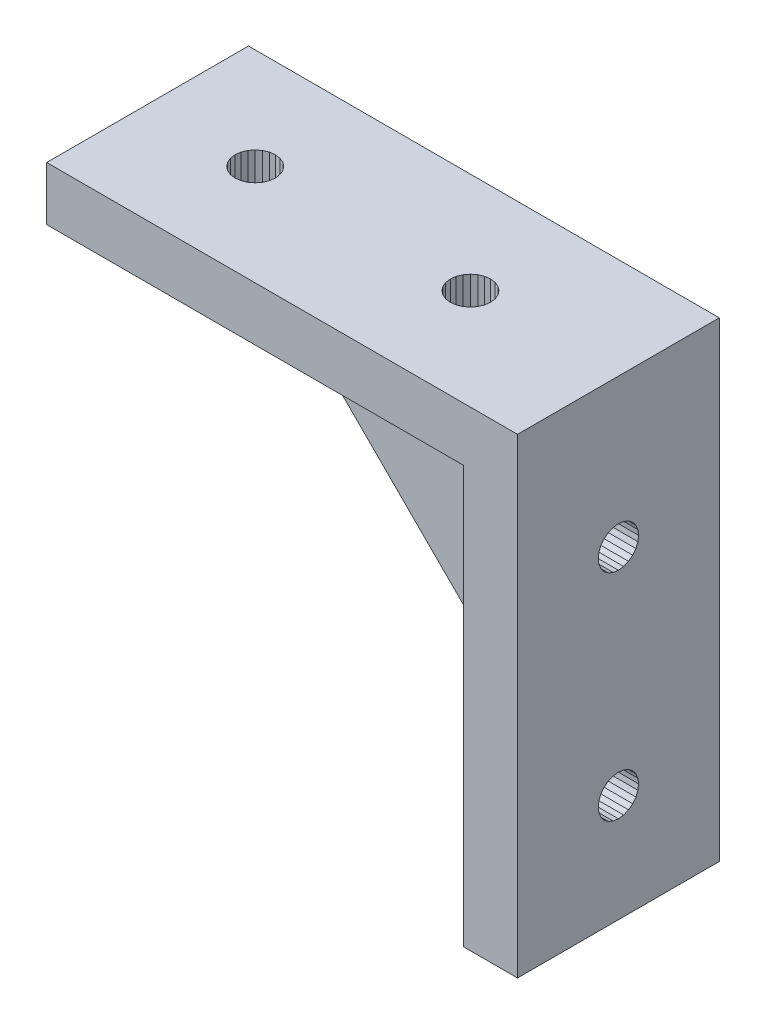
SolidWorks part; units mm, degrees
ref_plane "Front Plane" through (0, 0, 0) normal (0, 0, 1) x (1, 0, 0)
ref_plane "Top Plane" through (0, 0, 0) normal (0, 1, 0) x (1, 0, 0)
ref_plane "Right Plane" through (0, 0, 0) normal (1, 0, 0) x (0, 0, -1)
ref_plane "Plane4" through (0, 0, 10) normal (0, 0, -1) x (-1, 0, 0)
sketch "Sketch1" plane through (0, 0, 10) normal (0, 0, -1) x (-1, 0, 0)
  line L0 (-25, -35) -> (10, -35)
  line L1 (10, -35) -> (10, -4)
  line L2 (10, -4) -> (-25, -4)
  line L3 (-25, -4) -> (-25, -35)
  dimension "D1" = 35
  dimension "D2" = 31
extrude "Boss-Extrude1" add sketch "Sketch1" against normal blind 15
sketch "Sketch2" plane through (0, 0, 10) normal (0, 0, -1) x (-1, 0, 0)
  line L0 (10, -4) -> (-21, -35)
  line L1 (-21, -35) -> (10, -35)
  line L2 (10, -35) -> (10, -4)
  line L3 (-25, -4) -> (-25, -35) construction
  line L4 (-25, -35) -> (10, -35) construction
  dimension "D1" = 4
  dimension "D2" = 35
  dimension "D3" = 31
extrude "Cut-Extrude1" cut sketch "Sketch2" against normal blind 4
sketch "Sketch3" plane through (0, -4, 0) normal (0, 1, 0) x (-1, 0, 0)
  line L0 (10, 10) -> (-25, 10)
  line L1 (-25, 10) -> (-25, 25)
  line L2 (-25, 25) -> (10, 25)
  line L3 (10, 25) -> (10, 10)
  line L4 (10, 25) -> (10, 14) construction
  line L5 (10, 10) -> (-25, 10) construction
  dimension "D1" = 35
  dimension "D2" = 15
extrude "Boss-Extrude2" add sketch "Sketch3" along normal blind 4
sketch "Sketch4" plane through (-10, 0, 0) normal (-1, 0, 0) x (0, 0, 1)
  line L0 (25, -35) -> (25, -4)
  line L1 (25, -4) -> (14, -4)
  line L2 (14, -4) -> (14, -35)
  line L3 (14, -35) -> (25, -35)
  line L4 (25, -35) -> (25, 0) construction
  line L5 (25, -35) -> (14, -35) construction
  dimension "D1" = 11
  dimension "D2" = 31
extrude "Cut-Extrude2" cut sketch "Sketch4" against normal blind 31
sketch "Sketch5" plane through (0, -4, 0) normal (0, -1, 0) x (1, 0, 0)
  line L0 (-2.75, 16.201) -> (-2.3882, 16.0511)
  line L1 (-2.3882, 16.0511) -> (-2, 16)
  line L2 (-2, 16) -> (-1.6118, 16.0511)
  line L3 (-1.6118, 16.0511) -> (-1.25, 16.201)
  line L4 (-1.25, 16.201) -> (-0.9393, 16.4393)
  line L5 (-0.9393, 16.4393) -> (-0.701, 16.75)
  line L6 (-0.701, 16.75) -> (-0.5511, 17.1118)
  line L7 (-0.5511, 17.1118) -> (-0.5, 17.5)
  line L8 (-0.5, 17.5) -> (-0.5511, 17.8882)
  line L9 (-0.5511, 17.8882) -> (-0.701, 18.25)
  line L10 (-0.701, 18.25) -> (-0.9393, 18.5607)
  line L11 (-0.9393, 18.5607) -> (-1.25, 18.799)
  line L12 (-1.25, 18.799) -> (-1.6118, 18.9489)
  line L13 (-1.6118, 18.9489) -> (-2, 19)
  line L14 (-2, 19) -> (-2.3882, 18.9489)
  line L15 (-2.3882, 18.9489) -> (-2.75, 18.799)
  line L16 (-2.75, 18.799) -> (-3.0607, 18.5607)
  line L17 (-3.0607, 18.5607) -> (-3.299, 18.25)
  line L18 (-3.299, 18.25) -> (-3.4489, 17.8882)
  line L19 (-3.4489, 17.8882) -> (-3.5, 17.5)
  line L20 (-3.5, 17.5) -> (-3.4489, 17.1118)
  line L21 (-3.4489, 17.1118) -> (-3.299, 16.75)
  line L22 (-3.299, 16.75) -> (-3.0607, 16.4393)
  line L23 (-3.0607, 16.4393) -> (-2.75, 16.201)
  line L24 (-10, 25) -> (-10, 14) construction
  line L25 (21, 14) -> (-10, 14) construction
  dimension "D1" = 6.5
  dimension "D2" = 6.5511
  dimension "D3" = 6.701
  dimension "D4" = 6.9393
  dimension "D5" = 7.25
  dimension "D6" = 7.6118
  dimension "D7" = 8
  dimension "D8" = 8.3882
  dimension "D9" = 8.75
  dimension "D10" = 9.0607
  dimension "D11" = 9.299
  dimension "D12" = 9.4489
  dimension "D13" = 9.5
  dimension "D14" = 2
  dimension "D15" = 2.0511
  dimension "D16" = 2.201
  dimension "D17" = 2.4393
  dimension "D18" = 2.75
  dimension "D19" = 3.1118
  dimension "D20" = 3.5
  dimension "D21" = 3.8882
  dimension "D22" = 4.25
  dimension "D23" = 4.5607
  dimension "D24" = 4.799
  dimension "D25" = 4.9489
  dimension "D26" = 5
extrude "Cut-Extrude3" cut sketch "Sketch5" against normal through all
sketch "Sketch6" plane through (21, 0, 0) normal (-1, 0, 0) x (0, 0, 1)
  line L0 (17.1118, -28.4489) -> (17.5, -28.5)
  line L1 (17.5, -28.5) -> (17.8882, -28.4489)
  line L2 (17.8882, -28.4489) -> (18.25, -28.299)
  line L3 (18.25, -28.299) -> (18.5607, -28.0607)
  line L4 (18.5607, -28.0607) -> (18.799, -27.75)
  line L5 (18.799, -27.75) -> (18.9489, -27.3882)
  line L6 (18.9489, -27.3882) -> (19, -27)
  line L7 (19, -27) -> (18.9489, -26.6118)
  line L8 (18.9489, -26.6118) -> (18.799, -26.25)
  line L9 (18.799, -26.25) -> (18.5607, -25.9393)
  line L10 (18.5607, -25.9393) -> (18.25, -25.701)
  line L11 (18.25, -25.701) -> (17.8882, -25.5511)
  line L12 (17.8882, -25.5511) -> (17.5, -25.5)
  line L13 (17.5, -25.5) -> (17.1118, -25.5511)
  line L14 (17.1118, -25.5511) -> (16.75, -25.701)
  line L15 (16.75, -25.701) -> (16.4393, -25.9393)
  line L16 (16.4393, -25.9393) -> (16.201, -26.25)
  line L17 (16.201, -26.25) -> (16.0511, -26.6118)
  line L18 (16.0511, -26.6118) -> (16, -27)
  line L19 (16, -27) -> (16.0511, -27.3882)
  line L20 (16.0511, -27.3882) -> (16.201, -27.75)
  line L21 (16.201, -27.75) -> (16.4393, -28.0607)
  line L22 (16.4393, -28.0607) -> (16.75, -28.299)
  line L23 (16.75, -28.299) -> (17.1118, -28.4489)
  line L24 (14, -35) -> (25, -35) construction
  line L25 (25, -35) -> (25, -4) construction
  dimension "D1" = 6
  dimension "D2" = 6.0511
  dimension "D3" = 6.201
  dimension "D4" = 6.4393
  dimension "D5" = 6.75
  dimension "D6" = 7.1118
  dimension "D7" = 7.5
  dimension "D8" = 7.8882
  dimension "D9" = 8.25
  dimension "D10" = 8.5607
  dimension "D11" = 8.799
  dimension "D12" = 8.9489
  dimension "D13" = 9
  dimension "D14" = 6.5
  dimension "D15" = 6.5511
  dimension "D16" = 6.701
  dimension "D17" = 6.9393
  dimension "D18" = 7.25
  dimension "D19" = 7.6118
  dimension "D20" = 8
  dimension "D21" = 8.3882
  dimension "D22" = 8.75
  dimension "D23" = 9.0607
  dimension "D24" = 9.299
  dimension "D25" = 9.4489
  dimension "D26" = 9.5
extrude "Cut-Extrude4" cut sketch "Sketch6" against normal through all
sketch "Sketch7" plane through (21, 0, 0) normal (-1, 0, 0) x (0, 0, 1)
  line L0 (16.201, -11.75) -> (16.4393, -12.0607)
  line L1 (16.4393, -12.0607) -> (16.75, -12.299)
  line L2 (16.75, -12.299) -> (17.1118, -12.4489)
  line L3 (17.1118, -12.4489) -> (17.5, -12.5)
  line L4 (17.5, -12.5) -> (17.8882, -12.4489)
  line L5 (17.8882, -12.4489) -> (18.25, -12.299)
  line L6 (18.25, -12.299) -> (18.5607, -12.0607)
  line L7 (18.5607, -12.0607) -> (18.799, -11.75)
  line L8 (18.799, -11.75) -> (18.9489, -11.3882)
  line L9 (18.9489, -11.3882) -> (19, -11)
  line L10 (19, -11) -> (18.9489, -10.6118)
  line L11 (18.9489, -10.6118) -> (18.799, -10.25)
  line L12 (18.799, -10.25) -> (18.5607, -9.9393)
  line L13 (18.5607, -9.9393) -> (18.25, -9.701)
  line L14 (18.25, -9.701) -> (17.8882, -9.5511)
  line L15 (17.8882, -9.5511) -> (17.5, -9.5)
  line L16 (17.5, -9.5) -> (17.1118, -9.5511)
  line L17 (17.1118, -9.5511) -> (16.75, -9.701)
  line L18 (16.75, -9.701) -> (16.4393, -9.9393)
  line L19 (16.4393, -9.9393) -> (16.201, -10.25)
  line L20 (16.201, -10.25) -> (16.0511, -10.6118)
  line L21 (16.0511, -10.6118) -> (16, -11)
  line L22 (16, -11) -> (16.0511, -11.3882)
  line L23 (16.0511, -11.3882) -> (16.201, -11.75)
  dimension "D1" = 0.3618
  dimension "D2" = 0.75
  dimension "D3" = 1.1382
  dimension "D4" = 1.5
  dimension "D5" = 1.8107
  dimension "D6" = 2.049
  dimension "D7" = 2.1989
  dimension "D8" = 2.25
  dimension "D9" = 0.3107
  dimension "D10" = 0.549
  dimension "D11" = 0.6989
  dimension "D12" = 0.75
  dimension "D13" = 15.9489
  dimension "D14" = 16
  dimension "D15" = 16.1498
  dimension "D16" = 16.3882
  dimension "D17" = 16.6989
  dimension "D18" = 17.0607
  dimension "D19" = 17.4489
  dimension "D20" = 17.8371
  dimension "D21" = 18.1989
  dimension "D22" = 18.5095
  dimension "D23" = 18.7479
  dimension "D24" = 18.8978
  dimension "D25" = 18.9489
extrude "Cut-Extrude5" cut sketch "Sketch7" against normal through all
sketch "Sketch8" plane through (0, 0, 0) normal (0, 1, 0) x (-1, 0, 0)
  line L0 (-12.701, 16.75) -> (-12.5511, 17.1118)
  line L1 (-12.5511, 17.1118) -> (-12.5, 17.5)
  line L2 (-12.5, 17.5) -> (-12.5511, 17.8882)
  line L3 (-12.5511, 17.8882) -> (-12.701, 18.25)
  line L4 (-12.701, 18.25) -> (-12.9393, 18.5607)
  line L5 (-12.9393, 18.5607) -> (-13.25, 18.799)
  line L6 (-13.25, 18.799) -> (-13.6118, 18.9489)
  line L7 (-13.6118, 18.9489) -> (-14, 19)
  line L8 (-14, 19) -> (-14.3882, 18.9489)
  line L9 (-14.3882, 18.9489) -> (-14.75, 18.799)
  line L10 (-14.75, 18.799) -> (-15.0607, 18.5607)
  line L11 (-15.0607, 18.5607) -> (-15.299, 18.25)
  line L12 (-15.299, 18.25) -> (-15.4489, 17.8882)
  line L13 (-15.4489, 17.8882) -> (-15.5, 17.5)
  line L14 (-15.5, 17.5) -> (-15.4489, 17.1118)
  line L15 (-15.4489, 17.1118) -> (-15.299, 16.75)
  line L16 (-15.299, 16.75) -> (-15.0607, 16.4393)
  line L17 (-15.0607, 16.4393) -> (-14.75, 16.201)
  line L18 (-14.75, 16.201) -> (-14.3882, 16.0511)
  line L19 (-14.3882, 16.0511) -> (-14, 16)
  line L20 (-14, 16) -> (-13.6118, 16.0511)
  line L21 (-13.6118, 16.0511) -> (-13.25, 16.201)
  line L22 (-13.25, 16.201) -> (-12.9393, 16.4393)
  line L23 (-12.9393, 16.4393) -> (-12.701, 16.75)
  dimension "D1" = 13
  dimension "D2" = 13.0511
  dimension "D3" = 13.201
  dimension "D4" = 13.4393
  dimension "D5" = 13.75
  dimension "D6" = 14.1118
  dimension "D7" = 14.5
  dimension "D8" = 14.8882
  dimension "D9" = 15.25
  dimension "D10" = 15.5607
  dimension "D11" = 15.799
  dimension "D12" = 15.9489
  dimension "D13" = 16
  dimension "D14" = 0.2384
  dimension "D15" = 0.549
  dimension "D16" = 0.9108
  dimension "D17" = 1.299
  dimension "D18" = 1.6873
  dimension "D19" = 2.049
  dimension "D20" = 2.3597
  dimension "D21" = 2.5981
  dimension "D22" = 2.7479
  dimension "D23" = 2.799
  dimension "D24" = 0.1498
  dimension "D25" = 0.201
extrude "Cut-Extrude6" cut sketch "Sketch8" against normal through all
